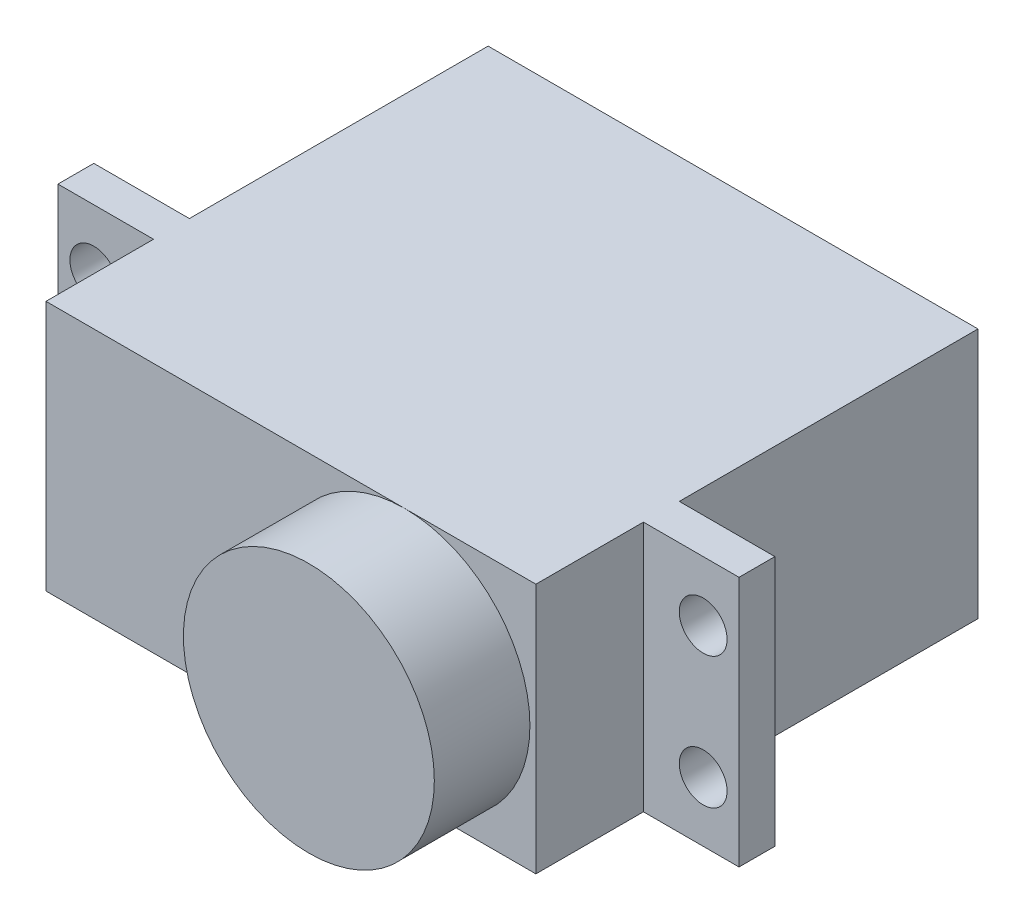
SolidWorks part; units mm, degrees
ref_plane "Front Plane" through (0, 0, 0) normal (0, 0, 1) x (1, 0, 0)
ref_plane "Top Plane" through (0, 0, 0) normal (0, 1, 0) x (1, 0, 0)
ref_plane "Right Plane" through (0, 0, 0) normal (1, 0, 0) x (0, 0, -1)
sketch "Sketch1" plane through (0, 0, 0) normal (0, 0, 1) x (1, 0, 0)
  line L1 (-45.6018, 5.2565) -> (-4.6018, 5.2565)
  line L2 (-45.6018, 5.2565) -> (-45.6018, -15.7435)
  line L3 (-45.6018, -15.7435) -> (-4.6018, -15.7435)
  line L4 (-4.6018, 5.2565) -> (-4.6018, -15.7435)
  dimension "D1" = 21
  dimension "D2" = 41
extrude "Boss-Extrude1" add sketch "Sketch1" along normal blind 25
sketch "Sketch4" plane through (0, 0, 25) normal (0, 0, 1) x (1, 0, 0)
  line L0 (-4.6018, 5.2565) -> (-45.6018, 5.2565)
  line L1 (-4.6018, 5.2565) -> (3.3982, 5.2565)
  line L2 (-45.6018, -15.7435) -> (-4.6018, -15.7435)
  line L3 (-4.6018, -15.7435) -> (3.3982, -15.7435)
  line L4 (3.3982, 5.2565) -> (3.3982, -15.7435)
  line L5 (-45.6018, 5.2565) -> (-53.6018, 5.2565)
  line L7 (-45.6018, -15.7435) -> (-53.6018, -15.7435)
  line L8 (-53.6018, 5.2565) -> (-53.6018, -15.7435)
  dimension "D1" = 21
  dimension "D2" = 8
  dimension "D3" = 8
extrude "Boss-Extrude2" add sketch "Sketch4" along normal blind 3
sketch "Sketch5" plane through (0, 0, 28) normal (0, 0, 1) x (1, 0, 0)
  line L0 (-45.6018, 5.2565) -> (-4.6018, 5.2565)
  line L1 (3.3982, 5.2565) -> (-53.6018, 5.2565) construction
  line L2 (-45.6018, 5.2565) -> (-45.6018, -15.7435)
  line L3 (-53.6018, -15.7435) -> (3.3982, -15.7435) construction
  line L4 (-45.6018, -15.7435) -> (-4.6018, -15.7435)
  line L5 (-4.6018, -15.7435) -> (-4.6018, 5.2565)
extrude "Boss-Extrude3" add sketch "Sketch5" along normal blind 9
sketch "Sketch6" plane through (0, 0, 28) normal (0, 0, 1) x (1, 0, 0)
  line L0 (-53.6018, -15.7435) -> (-45.6018, -15.7435) construction
  line L1 (-53.6018, 5.2565) -> (-53.6018, -15.7435) construction
  line L2 (-45.6018, 5.2565) -> (-53.6018, 5.2565) construction
  circle A0 centre (-50.6018, -10.7435) radius 2
  circle A1 centre (-50.6018, 0.2565) radius 2
  point P8 (-49.6018, 5.2565)
  dimension "D3" = 4
  dimension "D4" = 4
  dimension "D1" = 5
  dimension "D2" = 3
  dimension "D5" = 3
  dimension "D6" = 5
extrude "Cut-Extrude1" cut sketch "Sketch6" against normal blind 9
sketch "Sketch7" plane through (0, 0, 28) normal (0, 0, 1) x (1, 0, 0)
  line L0 (-4.6018, -15.7435) -> (3.3982, -15.7435) construction
  line L1 (3.3982, -15.7435) -> (3.3982, 5.2565) construction
  line L2 (3.3982, 5.2565) -> (-4.6018, 5.2565) construction
  circle A0 centre (0.3982, -10.7435) radius 2
  circle A1 centre (0.3982, 0.2565) radius 2
  dimension "D1" = 4
  dimension "D2" = 4
  dimension "D3" = 5
  dimension "D4" = 3
  dimension "D5" = 5
  dimension "D6" = 3
extrude "Cut-Extrude2" cut sketch "Sketch7" against normal blind 9
sketch "Sketch8" plane through (0, 0, 37) normal (0, 0, 1) x (1, 0, 0)
  line L0 (-4.6018, -5.2435) -> (-45.6018, -5.2435) construction
  line L1 (-4.6018, -15.7435) -> (-4.6018, 5.2565) construction
  line L2 (-45.6018, 5.2565) -> (-45.6018, -15.7435) construction
  circle A0 centre (-15.6018, -5.2435) radius 10.5
  dimension "D1" = 21
  dimension "D2" = 11
extrude "Boss-Extrude4" add sketch "Sketch8" along normal blind 8
